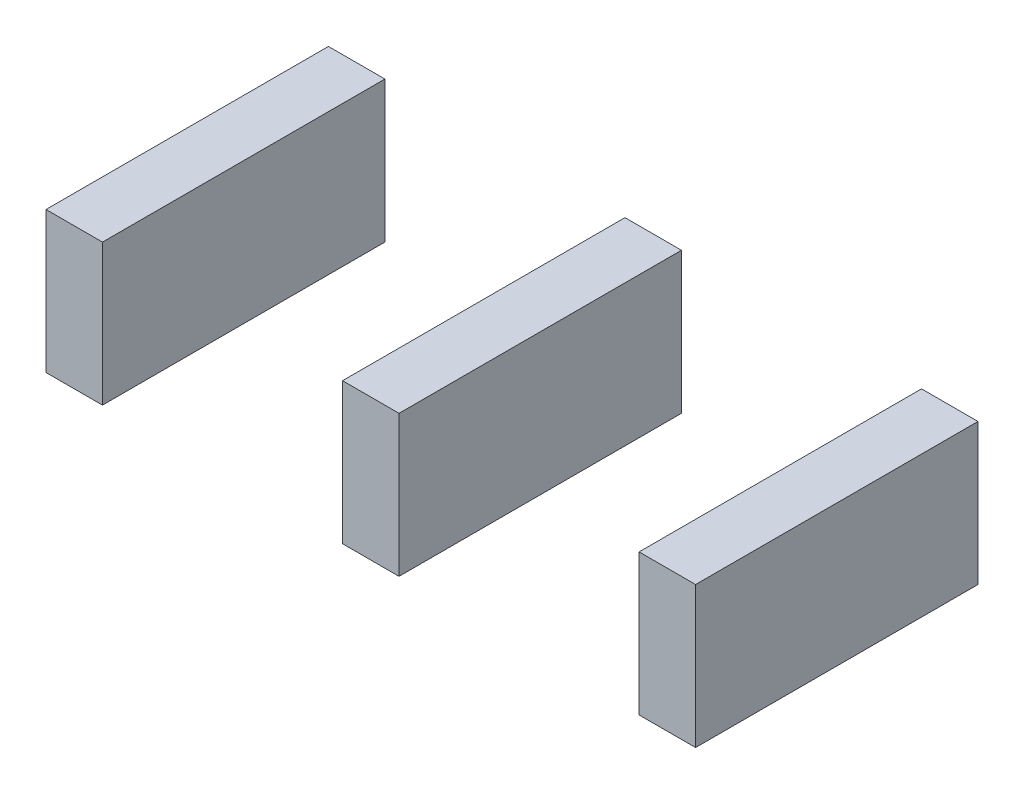
SolidWorks part; units mm, degrees
material "AISI 316 Stainless Steel Sheet (SS)"
ref_plane "Front Plane" through (0, 0, 0) normal (0, 0, 1) x (1, 0, 0)
ref_plane "Top Plane" through (0, 0, 0) normal (0, 1, 0) x (1, 0, 0)
ref_plane "Right Plane" through (0, 0, 0) normal (1, 0, 0) x (0, 0, -1)
sketch "Sketch1" plane through (0, 0, 0) normal (0, 0, 1) x (1, 0, 0)
  line L0 (3.8, 1) -> (3.8, -1)
  line L1 (-0.4, 1) -> (0.4, 1)
  line L2 (-0.4, 1) -> (-0.4, -1)
  line L3 (-0.4, -1) -> (0.4, -1)
  line L4 (0.4, 1) -> (0.4, -1)
  line L5 (3.8, 1) -> (4.6, 1)
  line L6 (4.6, 1) -> (4.6, -1)
  line L7 (3.8, -1) -> (4.6, -1)
  line L8 (-4.6, 1) -> (-4.6, -1)
  line L9 (-4.6, 1) -> (-3.8, 1)
  line L10 (-3.8, 1) -> (-3.8, -1)
  line L11 (-4.6, -1) -> (-3.8, -1)
  point P4 (0.4, 0)
  point P6 (0, -1)
  dimension "D1" = 0.8
  dimension "D2" = 2
  dimension "D3" = 2
  dimension "D4" = 2
extrude "Boss-Extrude1" add sketch "Sketch1" along normal blind 4
